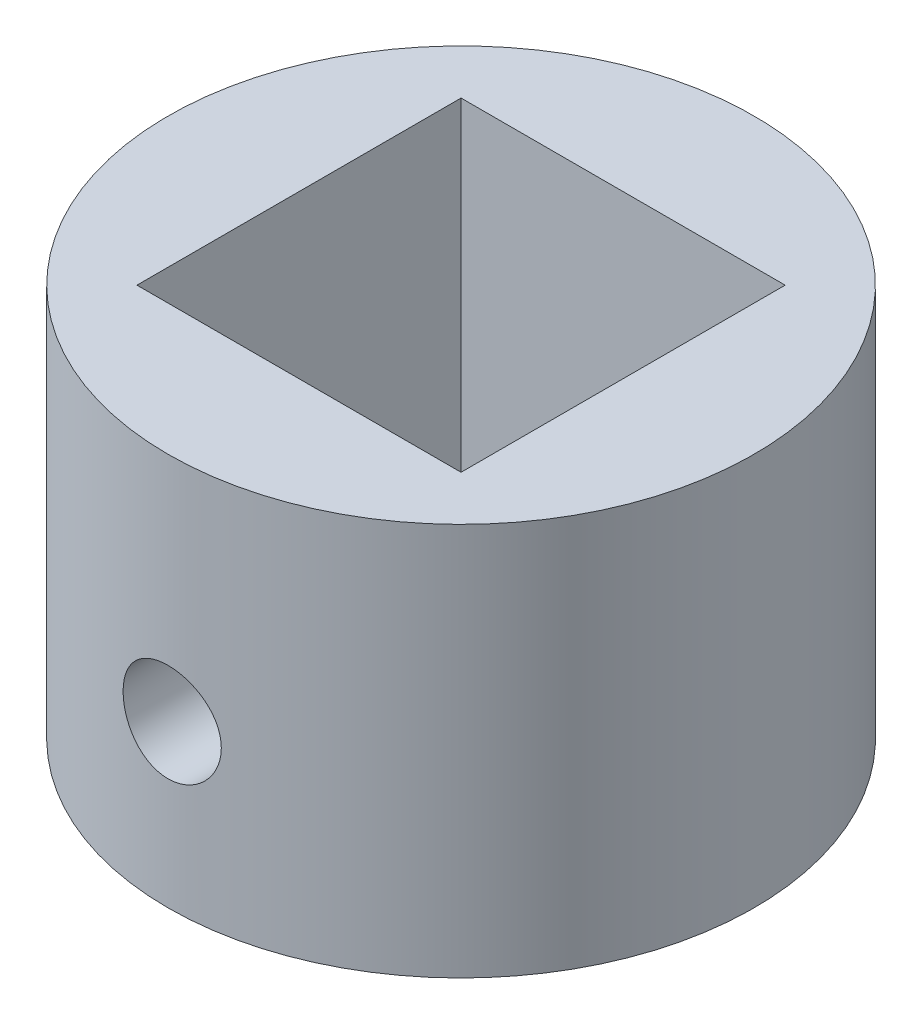
SolidWorks part; units mm, degrees
ref_plane "Front Plane" through (0, 0, 0) normal (0, 0, 1) x (1, 0, 0)
ref_plane "Top Plane" through (0, 0, 0) normal (0, 1, 0) x (1, 0, 0)
ref_plane "Right Plane" through (0, 0, 0) normal (1, 0, 0) x (0, 0, -1)
sketch "Sketch1" plane through (0, 0, 0) normal (0, 1, 0) x (1, 0, 0)
  line L1 (-4.95, -4.95) -> (4.95, -4.95)
  line L2 (-4.95, -4.95) -> (-4.95, 4.95)
  line L3 (-4.95, 4.95) -> (4.95, 4.95)
  line L4 (4.95, -4.95) -> (4.95, 4.95)
  line L5 (-4.95, -4.95) -> (4.95, 4.95) construction
  line L6 (-4.95, 4.95) -> (4.95, -4.95) construction
  circle A1 centre (0, 0) radius 8.95
  dimension "D1" = 9.9
  dimension "D3" = 17.9
  dimension "D2" = 9.9
  dimension "D4" = 0
extrude "Boss-Extrude1" add sketch "Sketch1" along normal blind 12
sketch "Sketch4" plane through (0, 0, 0) normal (0, 0, 1) x (1, 0, 0)
  circle A0 centre (0, 4.9164) radius 1.5
  dimension "D1" = 3
extrude "Cut-Extrude2" cut sketch "Sketch4" against normal through all both and the other way through all
